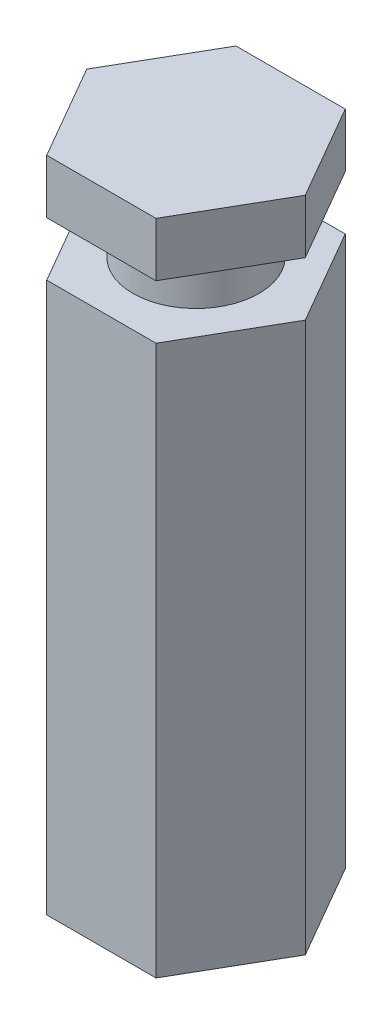
SolidWorks part; units mm, degrees
ref_plane "Płaszczyzna przednia" through (0, 0, 0) normal (0, 0, 1) x (1, 0, 0)
ref_plane "Płaszczyzna górna" through (0, 0, 0) normal (0, 1, 0) x (1, 0, 0)
ref_plane "Płaszczyzna prawa" through (0, 0, 0) normal (1, 0, 0) x (0, 0, -1)
sketch "Szkic2" plane through (0, 0, 0) normal (0, 1, 0) x (1, 0, 0)
  line L1 (12.1244, 0) -> (6.0622, 10.5)
  line L2 (6.0622, 10.5) -> (-6.0622, 10.5)
  line L3 (-6.0622, 10.5) -> (-12.1244, 0)
  line L4 (-12.1244, 0) -> (-6.0622, -10.5)
  line L5 (-6.0622, -10.5) -> (6.0622, -10.5)
  line L6 (6.0622, -10.5) -> (12.1244, 0)
  circle A0 centre (0, 0) radius 10.5 construction
  dimension "D1" = 21
  dimension "D2" = 10.5
extrude "Dodanie-wyciągnięcie1" add sketch "Szkic2" along normal blind 61
sketch "Szkic3" plane through (0, 61, 0) normal (0, 1, 0) x (1, 0, 0)
  circle A0 centre (0, 0) radius 7
  dimension "D1" = 14
extrude "Dodanie-wyciągnięcie2" add sketch "Szkic3" along normal blind 6
sketch "Szkic4" plane through (0, 67, 0) normal (0, 1, 0) x (1, 0, 0)
  line L1 (12.1244, 0) -> (6.0622, 10.5)
  line L2 (6.0622, 10.5) -> (-6.0622, 10.5)
  line L3 (-6.0622, 10.5) -> (-12.1244, 0)
  line L4 (-12.1244, 0) -> (-6.0622, -10.5)
  line L5 (-6.0622, -10.5) -> (6.0622, -10.5)
  line L6 (6.0622, -10.5) -> (12.1244, 0)
  circle A0 centre (0, 0) radius 10.5 construction
  dimension "D1" = 21
  dimension "D2" = 10.5
extrude "Dodanie-wyciągnięcie3" add sketch "Szkic4" along normal blind 6
